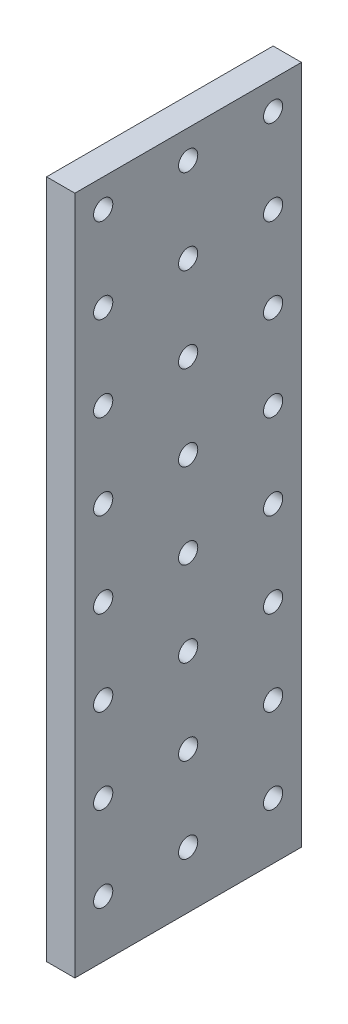
SolidWorks part; units mm, degrees
ref_plane "Front Plane" through (0, 0, 0) normal (0, 0, 1) x (1, 0, 0)
ref_plane "Top Plane" through (0, 0, 0) normal (0, 1, 0) x (1, 0, 0)
ref_plane "Right Plane" through (0, 0, 0) normal (1, 0, 0) x (0, 0, -1)
sketch "Sketch1" plane through (0, 0, 0) normal (1, 0, 0) x (0, 0, -1)
  line L1 (25.4, -76.2) -> (-25.4, -76.2)
  line L2 (25.4, -76.2) -> (25.4, 76.2)
  line L3 (25.4, 76.2) -> (-25.4, 76.2)
  line L4 (-25.4, -76.2) -> (-25.4, 76.2)
  line L5 (25.4, -76.2) -> (-25.4, 76.2) construction
  line L6 (25.4, 76.2) -> (-25.4, -76.2) construction
  point P0 (0, 0)
  dimension "D1" = 50.8
  dimension "D2" = 152.4
extrude "Boss-Extrude1" add sketch "Sketch1" against normal blind 6.35
sketch "Sketch2" plane through (0, 0, 0) normal (1, 0, 0) x (0, 0, -1)
  line L0 (25.4, 76.2) -> (-25.4, 76.2) construction
  line L1 (-25.4, 76.2) -> (-25.4, -76.2) construction
  line L2 (-25.4, -76.2) -> (25.4, -76.2) construction
  circle A0 centre (-19.05, 69.85) radius 2.1527
  circle A1 centre (0, 69.85) radius 2.1527
  circle A2 centre (19.05, 69.85) radius 2.1527
  circle A3 centre (0, 50.8) radius 2.1527
  circle A4 centre (19.05, 50.8) radius 2.1527
  circle A5 centre (0, 31.75) radius 2.1527
  circle A6 centre (19.05, 31.75) radius 2.1527
  circle A7 centre (0, 12.7) radius 2.1527
  circle A8 centre (19.05, 12.7) radius 2.1527
  circle A9 centre (0, -6.35) radius 2.1527
  circle A10 centre (19.05, -6.35) radius 2.1527
  circle A11 centre (0, -25.4) radius 2.1527
  circle A12 centre (19.05, -25.4) radius 2.1527
  circle A13 centre (0, -44.45) radius 2.1527
  circle A14 centre (19.05, -44.45) radius 2.1527
  circle A15 centre (0, -63.5) radius 2.1527
  circle A16 centre (19.05, -63.5) radius 2.1527
  circle A17 centre (-19.05, 50.8) radius 2.1527
  circle A18 centre (-19.05, 31.75) radius 2.1527
  circle A19 centre (-19.05, 12.7) radius 2.1527
  circle A20 centre (-19.05, -6.35) radius 2.1527
  circle A21 centre (-19.05, -25.4) radius 2.1527
  circle A22 centre (-19.05, -44.45) radius 2.1527
  circle A23 centre (-19.05, -63.5) radius 2.1527
  dimension "D1" = 4.3053
  dimension "D2" = 6.35
  dimension "D3" = 6.35
  dimension "D6" = 25.4
  dimension "D7" = 12.7
  dimension "D4" = 3
  dimension "D5" = 8
extrude "Cut-Extrude1" cut sketch "Sketch2" against normal through all
